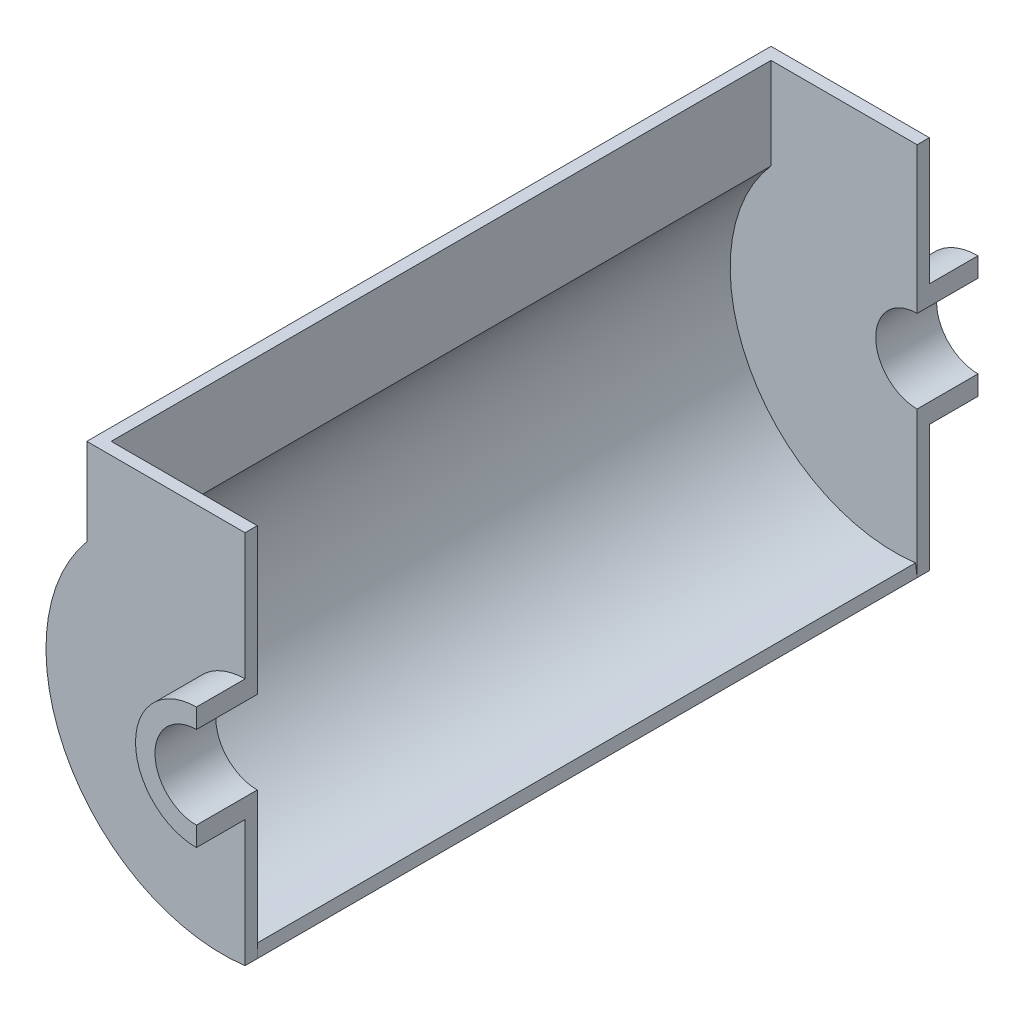
SolidWorks part; units mm, degrees
ref_plane "Front Plane" through (0, 0, 0) normal (0, 0, 1) x (1, 0, 0)
ref_plane "Top Plane" through (0, 0, 0) normal (0, 1, 0) x (1, 0, 0)
ref_plane "Right Plane" through (0, 0, 0) normal (1, 0, 0) x (0, 0, -1)
sketch "Sketch1" plane through (0, 0, 0) normal (0, 0, 1) x (1, 0, 0)
  line L0 (0, -25) -> (0, -17)
  line L1 (0, 17) -> (0, 25)
  arc A0 (0, 25) -> (0, -25) centre (0, 0) ccw
  arc A1 (0, 17) -> (0, -17) centre (0, 0) ccw
  point P7 (0, 0)
  dimension "D1" = 50
  dimension "D2" = 34
extrude "Boss-Extrude1" add sketch "Sketch1" along normal blind 20 and the other way blind 5
sketch "Sketch2" plane through (0, 0, 0) normal (0, 0, 1) x (1, 0, 0)
  line L0 (-76.9786, 0) -> (84.5972, 0) construction
  line L1 (0, 25) -> (0, 77)
  line L2 (0, -25) -> (0, -77)
  line L3 (0, 77) -> (-65, 77)
  line L5 (-65, 77) -> (-65, 41.2795)
  arc A0 (0, 25) -> (0, -25) centre (0, 0) ccw construction
  arc A1 (0, 25) -> (0, -25) centre (0, 0) ccw
  arc A3 (-65, 41.2795) -> (0, -77) centre (-9.2719, -5.0953) ccw
  point P9 (0, 0)
  point P11 (0, 0)
  dimension "D1" = 52
  dimension "D3" = 72.5
  dimension "D2" = 65
extrude "Boss-Extrude2" add sketch "Sketch2" against normal blind 5
ref_plane "Plane1" through (0, 0, -140.5) normal (0, 0, 1) x (1, 0, 0)
mirror "Mirror7" about plane through (0, 0, -140.5) normal (0, 0, 1) of bodies 102
sketch "Sketch3" plane through (0, 0, -5) normal (0, 0, -1) x (-1, 0, 0)
  line L0 (65, 77) -> (65, 41.2795) construction
  line L1 (65, 77) -> (65, 41.2795)
  line L2 (60, 77) -> (60, 39.4345)
  line L3 (65, 77) -> (60, 77)
  line L4 (0, -77) -> (0.6394, -72.0411)
  arc A0 (0, -77) -> (65, 41.2795) centre (9.2719, -5.0953) ccw construction
  arc A1 (0, -77) -> (65, 41.2795) centre (9.2719, -5.0953) ccw
  arc A2 (0.6394, -72.0411) -> (60, 39.4345) centre (9.2719, -5.0953) ccw
  dimension "D1" = 5
extrude "Boss-Extrude3" add sketch "Sketch3" along normal up to surface (271 mm away)
